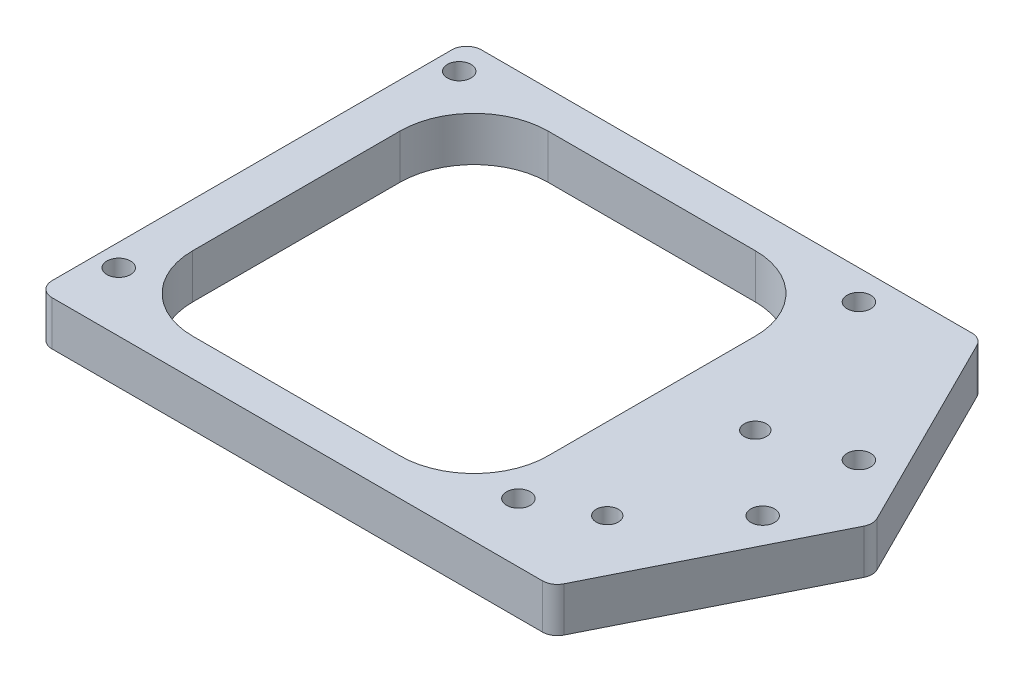
SolidWorks part; units mm, degrees
material "6061-T6 (SS)"
ref_plane "Front Plane" through (0, 0, 0) normal (0, 0, 1) x (1, 0, 0)
ref_plane "Top Plane" through (0, 0, 0) normal (0, 1, 0) x (1, 0, 0)
ref_plane "Right Plane" through (0, 0, 0) normal (1, 0, 0) x (0, 0, -1)
sketch "Sketch1" plane through (0, 0, 0) normal (0, 1, 0) x (1, 0, 0)
  line L0 (0, 14.5) -> (42, 14.5) construction
  line L1 (0, 0) -> (34.7484, 0)
  line L2 (0, 0) -> (0, 29)
  line L5 (42, 14.5) -> (34.7484, 29)
  line L6 (42, 14.5) -> (34.7484, 0)
  line L7 (0, 29) -> (34.7484, 29)
  dimension "D1" = 29
  dimension "D2" = 42
  dimension "D3" = 63.43
extrude "Boss-Extrude1" add sketch "Sketch1" along normal mid plane 3
sketch "Sketch2" plane through (0, 0, 0) normal (0, 1, 0) x (1, 0, 0)
  line L0 (0, 29) -> (0, 0) construction
  line L1 (3, 26.5) -> (27, 26.5)
  line L2 (3, 26.5) -> (3, 2.5)
  line L4 (27, 26.5) -> (27, 2.5)
  line L5 (0, 14.5) -> (42, 14.5) construction
  line L6 (34.7484, 29) -> (0, 29) construction
  line L7 (3, 2.5) -> (27, 2.5)
  point P14 (27, 14.5)
  point P15 (3, 14.5)
  dimension "D1" = 3
  dimension "D2" = 24
  dimension "D3" = 2.5
extrude "Cut-Extrude1" cut sketch "Sketch2" against normal through all both and the other way through all
fillet "Fillet1" radius 5 4 edges at (3, 0, -26.5) (27, 0, -26.5) (27, 0, -2.5) (3, 0, -2.5)
sketch "Sketch5" plane through (0, 1.5, 0) normal (0, 1, 0) x (1, 0, 0)
  line L0 (1.5, 27) -> (28.5, 27) construction
  line L1 (28.5, 27) -> (28.5, 4) construction
  line L2 (28.5, 4) -> (1.5, 4) construction
  line L3 (1.5, 4) -> (1.5, 27) construction
  line L4 (42, 14.5) -> (0, 14.5) construction
  line L7 (34.7484, 29) -> (0, 29) construction
  line L8 (0, 29) -> (0, 0) construction
  point P8 (37.7484, 11.25)
  point P16 (37.7484, 17.75)
  dimension "D1" = 3.25
  dimension "D2" = 2
  dimension "D3" = 1.5
  dimension "D4" = 23
  dimension "D5" = 27
  dimension "D6" = 37.7484
hole_wizard "M2x0.4 Tapped Hole1" positions "3DSketch4" profile "Sketch8" tap size "M2x0.4" standard "ANSI Metric" end condition through all
sketch3d "3DSketch4"
  point P0 (1.5, 1.5, -27)
  point P3 (28.5, 1.5, -27)
  point P6 (37.7484, 1.5, -17.75)
  point P9 (37.7484, 1.5, -11.25)
  point P12 (28.5, 1.5, -4)
  point P15 (1.5, 1.5, -4)
sketch "Sketch8" plane through (1.5, 1.5, -27) normal (1, 0, 0) x (0, 0, 1)
  line L0 (0, 0) -> (0, 3)
  line L1 (0, 3) -> (0.8, 3)
  line L2 (0.8, 3) -> (0.8, 0)
  line L5 (0.8, 0) -> (0, 0)
  line L11 (0, -6.35) -> (0, 107.95) construction
  dimension "Thru Tap Drill Dia." = 1.6
  dimension "Thru Tap Drill Depth" = 3
cosmetic thread "Hole Thread1" parameters "D2"=2
cosmetic thread "Hole Thread2" parameters "D2"=2
cosmetic thread "Hole Thread3" parameters "D2"=2
cosmetic thread "Hole Thread4" parameters "D2"=2
cosmetic thread "Hole Thread5" parameters "D2"=2
cosmetic thread "Hole Thread6" parameters "D2"=2
sketch "Sketch9" plane through (0, 1.5, 0) normal (0, 1, 0) x (1, 0, 0)
  line L3 (0, 0) -> (34.7484, 0) construction
  line L5 (0, 29) -> (0, 0) construction
  point P0 (32.5, 16)
  point P1 (32.5, 6)
  dimension "D1" = 32.5
  dimension "D2" = 16
  dimension "D3" = 6
  dimension "D4" = 32.5
hole_wizard "Ø1.5mm Dowel Hole1" positions "3DSketch5" profile "Sketch10" hole size "Ø1.5" standard "ANSI Metric" end condition through all
sketch3d "3DSketch5"
  point P0 (32.5, 1.5, -16)
  point P3 (32.5, 1.5, -6)
sketch "Sketch10" plane through (32.5, 1.5, -16) normal (1, 0, 0) x (0, 0, 1)
  line L0 (0, 0) -> (0, 3)
  line L1 (0, 3) -> (0.75, 3)
  line L2 (0.75, 3) -> (0.75, 0)
  line L5 (0.75, 0) -> (0, 0)
  line L11 (0, -6.35) -> (0, 107.95) construction
  dimension "Thru Hole Dia." = 1.5
  dimension "Thru Hole Depth" = 3
fillet "Fillet2" radius 1 5 edges at (0, 0, -29) (34.7484, 0, -29) (42, 0, -14.5) (34.7484, 0, 0) (0, 0, 0)
